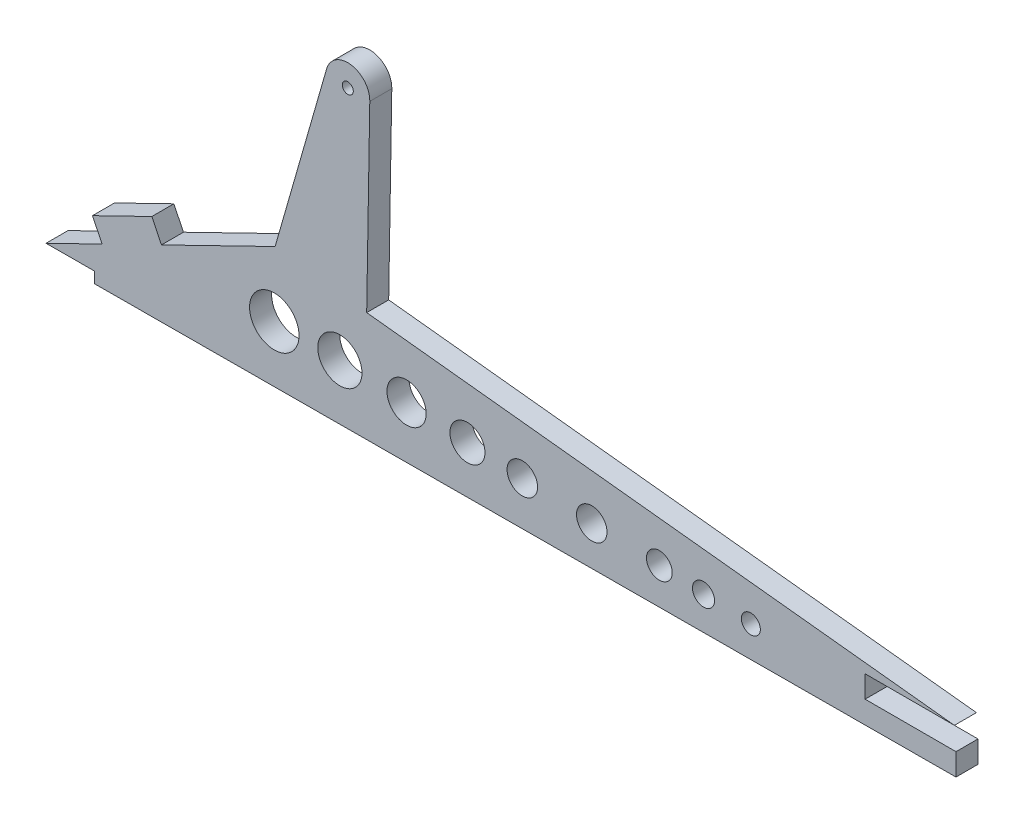
SolidWorks part; units mm, degrees
ref_plane "前视基准面" through (0, 0, 0) normal (0, 0, 1) x (1, 0, 0)
ref_plane "上视基准面" through (0, 0, 0) normal (0, 1, 0) x (1, 0, 0)
ref_plane "右视基准面" through (0, 0, 0) normal (1, 0, 0) x (0, 0, -1)
sketch "Model" plane through (0, 0, 0) normal (0, 0, 1) x (1, 0, 0)
  line L0 (7.0381, 6.2878) -> (6.1613, 8.0854)
  line L1 (6.1613, 8.0854) -> (11.5541, 10.7156)
  line L2 (11.5541, 10.7156) -> (12.4308, 8.918)
  line L3 (7.0381, 6.2878) -> (1.9393, 3.801)
  line L4 (12.4308, 8.918) -> (22.7538, 13.9529)
  line L5 (6.368, 2.819) -> (39.0801, 2.9522)
  line L6 (39.0801, 2.9522) -> (84.6132, 3.1386)
  line L7 (1.9393, 3.801) -> (6.364, 3.819)
  line L8 (6.368, 2.819) -> (6.364, 3.819)
  line L9 (22.7538, 13.9529) -> (27.4299, 30.2596)
  line L10 (31.356, 29.6736) -> (31.0739, 12.9133)
  line L11 (31.0739, 12.9133) -> (84.4694, 7.1386)
  line L12 (76.357, 5.1386) -> (84.6132, 5.1386)
  line L13 (76.357, 7.1386) -> (84.4694, 7.1386)
  line L14 (76.357, 5.1386) -> (76.357, 7.1386)
  line L15 (84.6132, 3.1386) -> (84.6132, 5.1386)
  circle A0 centre (29.3567, 29.7233) radius 0.5
  arc A1 (31.356, 29.6736) -> (27.4299, 30.2596) centre (29.3567, 29.7233) ccw
  circle A2 centre (34.6976, 7.6545) radius 1.783
  circle A3 centre (40.2282, 7.2652) radius 1.5906
  circle A4 centre (57.6624, 6.323) radius 1.1683
  circle A5 centre (61.6776, 6.0497) radius 1.006
  circle A6 centre (65.9754, 5.8705) radius 0.8624
  circle A7 centre (45.2143, 6.9441) radius 1.3868
  circle A8 centre (28.6362, 7.9435) radius 2.0077
  circle A9 centre (22.6801, 8.0227) radius 2.2462
  circle A10 centre (51.5238, 6.5569) radius 1.3868
extrude "凸台-拉伸1" add sketch "Model" along normal blind 2
